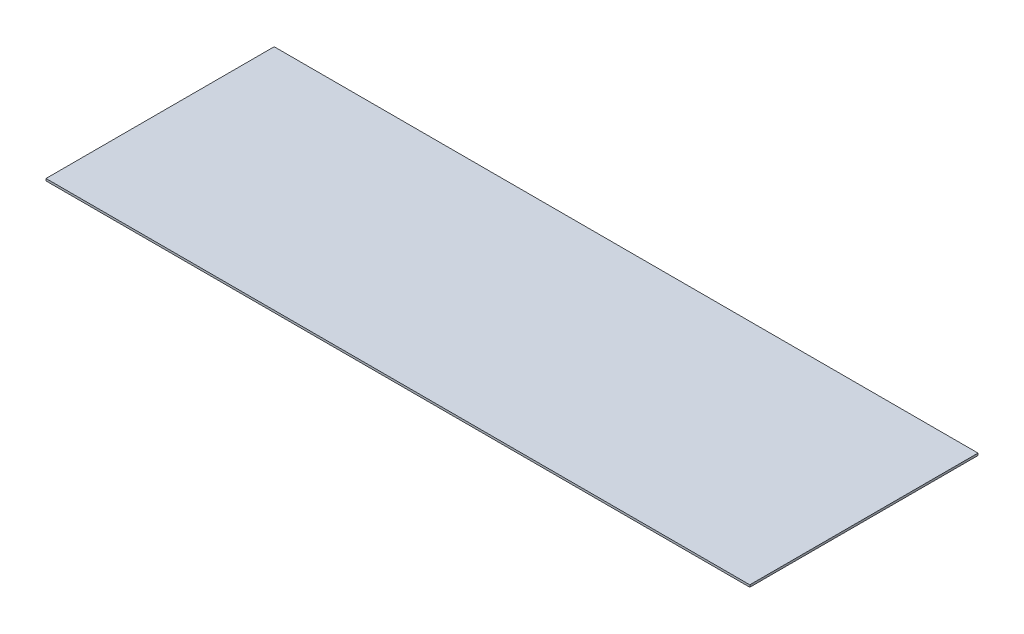
SolidWorks part; units mm, degrees
ref_plane "前视基准面" through (0, 0, 0) normal (0, 0, 1) x (1, 0, 0)
ref_plane "上视基准面" through (0, 0, 0) normal (0, 1, 0) x (1, 0, 0)
ref_plane "右视基准面" through (0, 0, 0) normal (1, 0, 0) x (0, 0, -1)
sketch "草图1" plane through (0, 0, 0) normal (0, 1, 0) x (1, 0, 0)
  line L1 (-493.5, 160) -> (493.5, 160)
  line L2 (-493.5, 160) -> (-493.5, -160)
  line L3 (-493.5, -160) -> (493.5, -160)
  line L4 (493.5, 160) -> (493.5, -160)
  line L5 (-493.5, 160) -> (493.5, -160) construction
  line L6 (-493.5, -160) -> (493.5, 160) construction
  point P0 (0, 0)
  dimension "D1" = 987
  dimension "D2" = 320
extrude "凸台-拉伸1" add sketch "草图1" along normal blind 3
